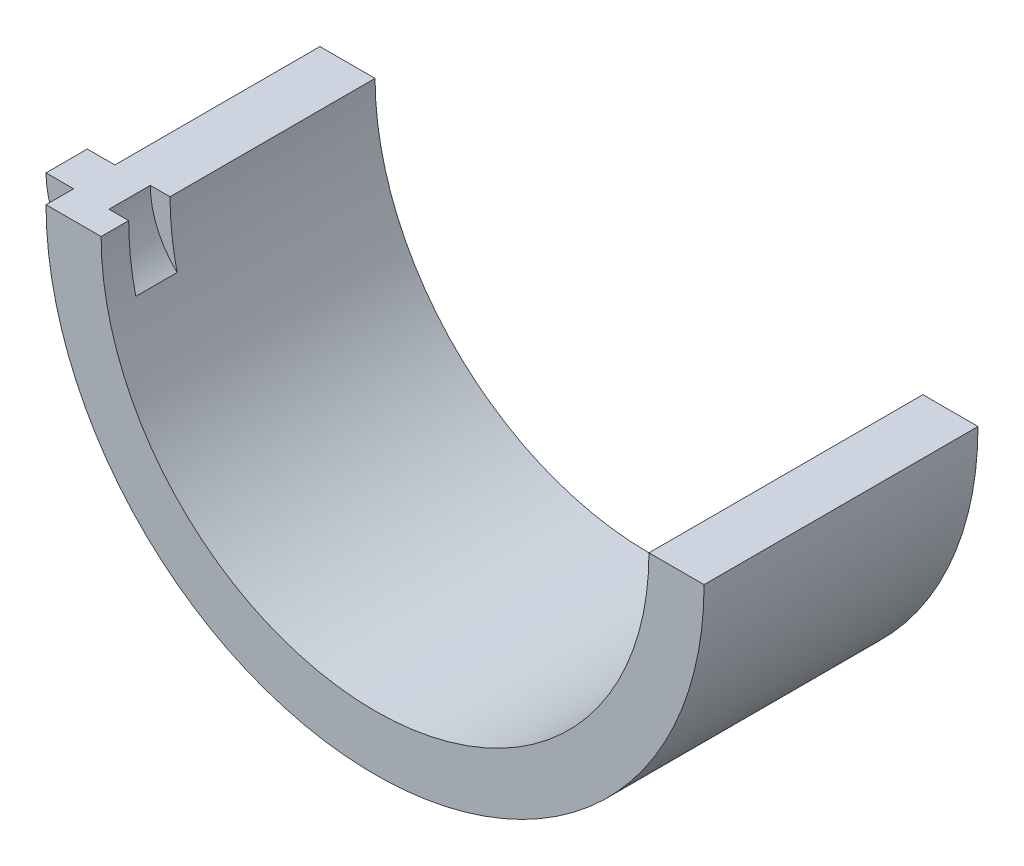
SolidWorks part; units mm, degrees
material "201 Annealed Stainless Steel (SS)"
ref_plane "Front Plane" through (0, 0, 0) normal (0, 0, 1) x (1, 0, 0)
ref_plane "Top Plane" through (0, 0, 0) normal (0, 1, 0) x (1, 0, 0)
ref_plane "Right Plane" through (0, 0, 0) normal (1, 0, 0) x (0, 0, -1)
sketch "Sketch1" plane through (0, 0, 0) normal (0, 0, 1) x (1, 0, 0)
  line L0 (0, 0) -> (-12.7, 0) construction
  line L1 (15.1638, 15.1638) -> (-15.1638, 15.1638) construction
  line L2 (-12.6238, 15.1638) -> (-15.1638, 15.1638)
  line L3 (12.6238, 15.1638) -> (15.1638, 15.1638)
  circle A0 centre (0, 15.1638) radius 15.1638 construction
  circle A1 centre (0, 15.1638) radius 12.6238 construction
  arc A2 (-15.1638, 15.1638) -> (15.1638, 15.1638) centre (0, 15.1638) ccw
  arc A3 (12.6238, 15.1638) -> (-12.6238, 15.1638) centre (0, 15.1638) cw
  dimension "D2" = 2.54
  dimension "D3" = 25.2476
  dimension "D1" = 12.7
extrude "Boss-Extrude1" add sketch "Sketch1" against normal blind 12.6238
sketch "Sketch2" plane through (0, 0, 0) normal (0, 1, 0) x (1, 0, 0)
  line L0 (15.1638, 0) -> (-15.1638, 12.6238) construction
  circle A0 centre (0, 6.3119) radius 1.4986
  dimension "D1" = 2.9972
extrude "Cut-Extrude1" [suppressed] cut sketch "Sketch2" along normal up to next
sketch "Sketch3" [suppressed] plane through (0, 15.7988, 0) normal (0, 1, 0) x (1, 0, 0)
  line L0 (12.6238, 6.3119) -> (12.2428, 6.3119) construction
  line L1 (12.6238, 12.6238) -> (12.6238, 0) construction
  line L2 (12.6235, 7.7613) -> (12.6235, 4.8625)
  arc A0 (12.6235, 7.7613) -> (12.6235, 4.8625) centre (12.2428, 6.3119) cw
  circle A1 centre (0, 6.3119) radius 1.4986 construction
  dimension "D1" = 0.0003
  dimension "D2" = 0.381
ref_plane "Plane1" through (0, 0, -6.3119) normal (0, 0, 1) x (1, 0, 0)
sketch "Sketch4" plane through (0, 0, -6.3119) normal (0, 0, 1) x (1, 0, 0)
  line L0 (15.1638, 15.1638) -> (12.6238, 15.1638) construction
  arc A0 (-12.6238, 15.1638) -> (12.6238, 15.1638) centre (0, 15.1663) ccw
  dimension "D1" = 0.0025
sweep "Cut-Sweep1" [suppressed] cut profiles "Sketch3" path "Sketch4"
ref_plane "Plane2" through (0, 0, -1.27) normal (0, 0, 1) x (1, 0, 0)
sketch "Sketch5" plane through (0, 0, -1.27) normal (0, 0, 1) x (1, 0, 0)
  line L0 (15.1638, 15.1638) -> (-15.1638, 15.1638) construction
  line L1 (15.1638, 15.1638) -> (16.4338, 15.1638) construction
  line L2 (16.4338, 15.1638) -> (16.4338, 18.2188) construction
  line L3 (0, 15.1638) -> (0, 0) construction
  line L4 (-15.1638, 15.1638) -> (-16.4338, 15.1638)
  arc A0 (15.1638, 15.1638) -> (14.8444, 12.0678) centre (0, 15.1638) cw construction
  arc A1 (16.4338, 15.1638) -> (14.8444, 12.0678) centre (12.6238, 15.1638) cw construction
  arc A2 (-15.1638, 15.1638) -> (15.1638, 15.1638) centre (0, 15.1638) ccw construction
  arc A3 (-12.6238, 15.1638) -> (12.6238, 15.1638) centre (0, 15.1638) ccw construction
  arc A4 (-16.4338, 15.1638) -> (-14.8444, 12.0678) centre (-12.6238, 15.1638) ccw
  arc A5 (-15.1638, 15.1638) -> (-14.8444, 12.0678) centre (0, 15.1638) ccw
  dimension "D1" = 1.27
  dimension "D2" = 3.055
extrude "Boss-Extrude2" add sketch "Sketch5" against normal blind 1.905 contours A4 A5 L4
sketch "Sketch6" plane through (0, 0, -1.27) normal (0, 0, 1) x (1, 0, 0)
  line L0 (12.6238, 15.1638) -> (-12.6238, 15.1638) construction
  line L1 (15.4155, 12.3038) -> (12.2956, 12.3038) construction
  line L2 (12.6238, 15.1638) -> (13.5316, 15.1638) construction
  line L3 (15.1638, 15.1638) -> (12.6238, 15.1638) construction
  line L5 (0, 15.1638) -> (0, 0) construction
  line L6 (-12.6238, 15.1638) -> (-13.5316, 15.1638)
  arc A0 (-12.6238, 15.1638) -> (12.6238, 15.1638) centre (0, 15.1638) ccw construction
  arc A1 (12.6238, 15.1638) -> (12.2956, 12.3038) centre (0, 15.1638) cw construction
  arc A2 (13.5316, 15.1638) -> (12.2956, 12.3038) centre (9.6049, 15.1638) cw construction
  arc A3 (-12.6238, 15.1638) -> (-12.2956, 12.3038) centre (0, 15.1638) ccw
  arc A4 (-13.5316, 15.1638) -> (-12.2956, 12.3038) centre (-9.6049, 15.1638) ccw
extrude "Cut-Extrude2" cut sketch "Sketch6" against normal blind 1.905 contours L6 A4 A3
